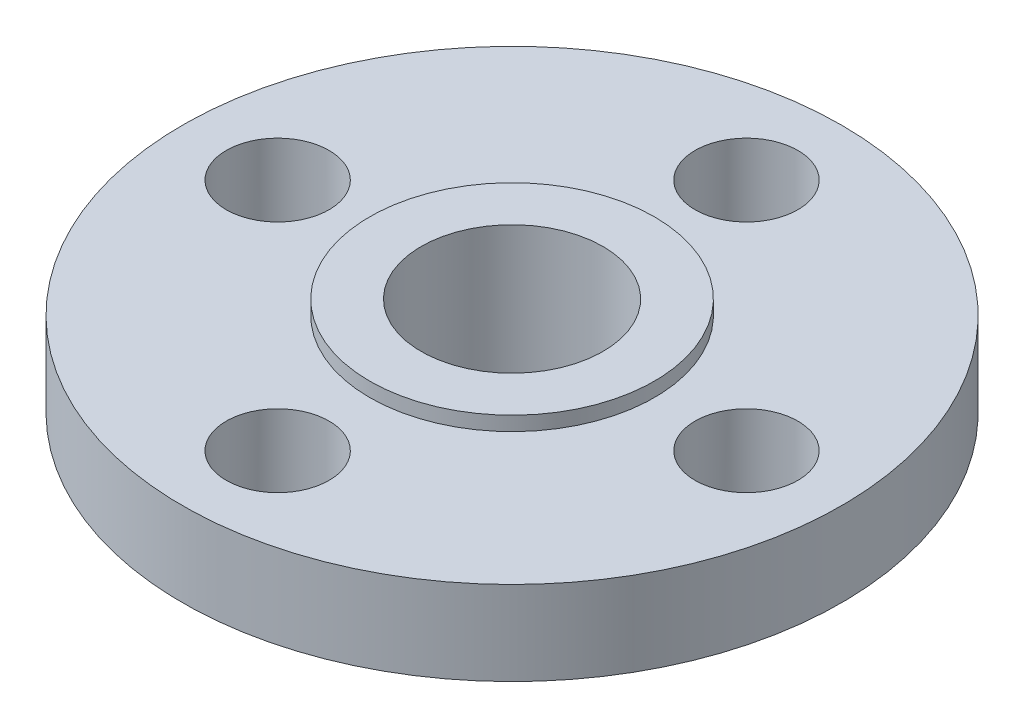
SolidWorks part; units mm, degrees
ref_plane "Front Plane" through (0, 0, 0) normal (0, 0, 1) x (1, 0, 0)
ref_plane "Top Plane" through (0, 0, 0) normal (0, 1, 0) x (1, 0, 0)
ref_plane "Right Plane" through (0, 0, 0) normal (1, 0, 0) x (0, 0, -1)
sketch "Sketch1" plane through (0, 0, 0) normal (0, 0, 1) x (1, 0, 0)
  line L0 (0, 0) -> (0, 25) construction
  line L1 (-17.25, 0) -> (-21.4596, 0)
  line L2 (-21.4596, 0) -> (-23.9408, 5.8452)
  line L3 (-23.9408, 5.8452) -> (-27.7185, 5.8452)
  line L4 (-27.7185, 5.8452) -> (-30.1996, 0)
  line L5 (-30.1996, 0) -> (-35, 0)
  line L6 (-35, 0) -> (-35, 6.35)
  line L7 (-35, 6.35) -> (-62.5, 6.35)
  line L8 (-62.5, 6.35) -> (-62.5, 22.3)
  line L9 (-62.5, 22.3) -> (-27, 22.3)
  line L10 (-27, 22.3) -> (-27, 25)
  line L11 (-27, 25) -> (-17.25, 25)
  line L12 (-17.25, 25) -> (-17.25, 0)
  line L13 (-27.7185, 5.8452) -> (-32.0541, 5.8452) construction
  line L14 (-23.9408, 5.8452) -> (-16.2921, 5.8452) construction
  point P18 (-25.8296, 5.8452)
  dimension "D1" = 25
  dimension "D2" = 15.95
  dimension "D3" = 6.35
  dimension "D4" = 17.25
  dimension "D5" = 27
  dimension "D6" = 35
  dimension "D7" = 25.8296
  dimension "D8" = 6.35
  dimension "D9" = 8.74
  dimension "D10" = 67
  dimension "D11" = 67
  dimension "D12" = 62.5
revolve "Revolve1" add sketch "Sketch1" angle 360 about L0
sketch "Sketch2" plane through (0, 22.3, 0) normal (0, 1, 0) x (1, 0, 0)
  circle A0 centre (-44.45, 0) radius 9.75
  circle A1 centre (0, 44.45) radius 9.75
  circle A2 centre (44.45, 0) radius 9.75
  circle A3 centre (0, -44.45) radius 9.75
  point P13 (0, 0)
  dimension "D1" = 19.5
  dimension "D2" = 44.45
  dimension "D3" = 4
extrude "Cut-Extrude1" cut sketch "Sketch2" against normal through all
